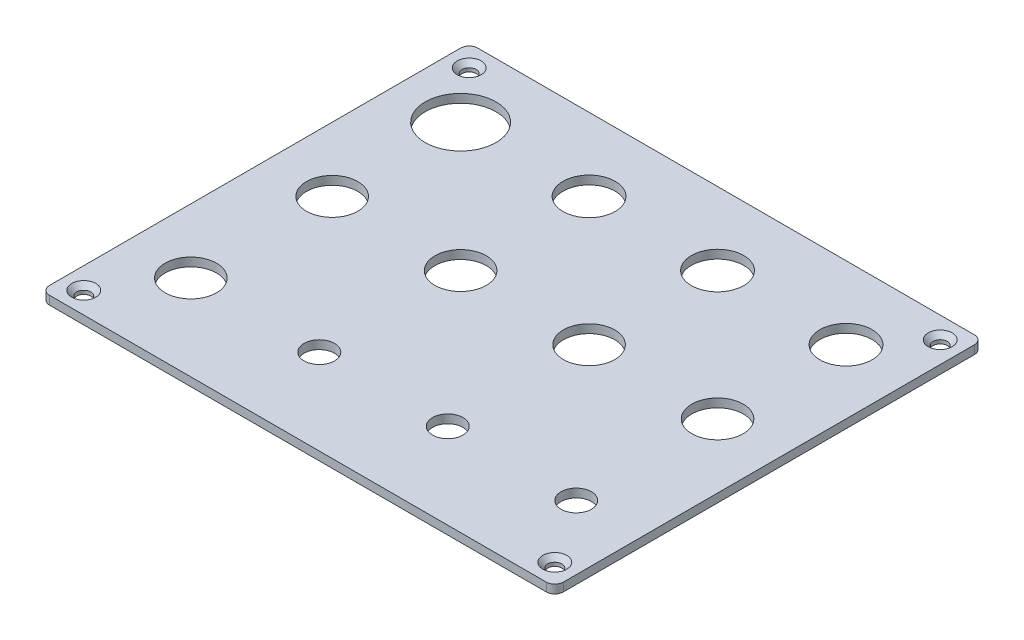
SolidWorks part; units mm, degrees
ref_plane "Front Plane" through (0, 0, 0) normal (0, 0, 1) x (1, 0, 0)
ref_plane "Top Plane" through (0, 0, 0) normal (0, 1, 0) x (1, 0, 0)
ref_plane "Right Plane" through (0, 0, 0) normal (1, 0, 0) x (0, 0, -1)
sketch "Bottom Plate" plane through (0, 0, 0) normal (0, 1, 0) x (1, 0, 0)
  line L1 (0, 0) -> (-120, 0)
  line L2 (0, 0) -> (0, 100)
  line L3 (0, 100) -> (-120, 100)
  line L4 (-120, 0) -> (-120, 100)
  dimension "D1" = 120
  dimension "D2" = 100
extrude "Bottom Plate EXT" add sketch "Bottom Plate" along normal blind 2
sketch "Middle Row" plane through (0, 2, 0) normal (0, 1, 0) x (1, 0, 0)
  line L0 (-120, 100) -> (-120, 0) construction
  line L1 (-120, 50) -> (0, 50) construction
  line L2 (0, 0) -> (0, 100) construction
  circle A0 centre (-105, 53) radius 6
  circle A1 centre (-75, 53) radius 6
  circle A2 centre (-45, 53) radius 6
  circle A3 centre (-15, 53) radius 6
  dimension "D1" = 12
  dimension "D2" = 30
  dimension "D6" = 30
  dimension "D3" = 30
  dimension "D4" = 15
  dimension "D5" = 3
extrude "Middle Row Cut" cut sketch "Middle Row" against normal through all
sketch "Top Row" plane through (0, 2, 0) normal (0, 1, 0) x (1, 0, 0)
  line L1 (-120, 100) -> (-120, 0) construction
  circle A0 centre (-105, 83) radius 8.25
  circle A1 centre (-75, 83) radius 6.1
  circle A2 centre (-45, 83) radius 6.1
  circle A3 centre (-15, 83) radius 6.1
  circle A6 centre (-105, 53) radius 6 construction
  dimension "D1" = 16.5
  dimension "D2" = 30
  dimension "D7" = 12.2
  dimension "D3" = 15
  dimension "D4" = 30
  dimension "D5" = 30
  dimension "D6" = 30
extrude "Top Row Cut" cut sketch "Top Row" against normal through all
sketch "Bottom Row" plane through (0, 2, 0) normal (0, 1, 0) x (1, 0, 0)
  line L1 (-120, 100) -> (-120, 0) construction
  circle A0 centre (-75, 20) radius 3.55
  circle A1 centre (-45, 20) radius 3.55
  circle A2 centre (-15, 20) radius 3.55
  circle A5 centre (-105, 20) radius 6
  circle A6 centre (-105, 53) radius 6 construction
  dimension "D1" = 7.1
  dimension "D2" = 33
  dimension "D3" = 30
  dimension "D4" = 30
  dimension "D5" = 30
  dimension "D6" = 15
extrude "Bottom Row Cut" cut sketch "Bottom Row" against normal through all
sketch "Plate Screws" plane through (0, 2, 0) normal (0, 1, 0) x (1, 0, 0)
  line L0 (0, 100) -> (-120, 100) construction
  line L1 (-120, 100) -> (-120, 0) construction
  line L2 (-120, 0) -> (0, 0) construction
  line L3 (0, 0) -> (0, 100) construction
  circle A0 centre (-115, 95) radius 1.65
  circle A1 centre (-5, 95) radius 1.65
  circle A2 centre (-5, 5) radius 1.65
  circle A3 centre (-115, 5) radius 1.65
  dimension "D1" = 3.3
  dimension "D2" = 5
  dimension "D3" = 5
  dimension "D4" = 5
  dimension "D5" = 5
extrude "Plate Screws Cut" cut sketch "Plate Screws" against normal through all
sketch "Plate Screw Head" plane through (0, 2, 0) normal (0, 1, 0) x (1, 0, 0)
  circle A0 centre (-115, 95) radius 2.8
  circle A1 centre (-5, 95) radius 2.8
  circle A2 centre (-5, 5) radius 2.8
  circle A3 centre (-115, 5) radius 2.8
  dimension "D1" = 5.6
extrude "Plate Screw Head Cut" cut sketch "Plate Screw Head" against normal blind 2 draft 45
fillet "Fillet1" radius 2 1 edges at (-120, 1, -100)
fillet "Fillet2" radius 2 1 edges at (0, 1, -100)
fillet "Fillet3" radius 2 1 edges at (0, 1, 0)
fillet "Fillet4" radius 2 1 edges at (-120, 1, 0)
